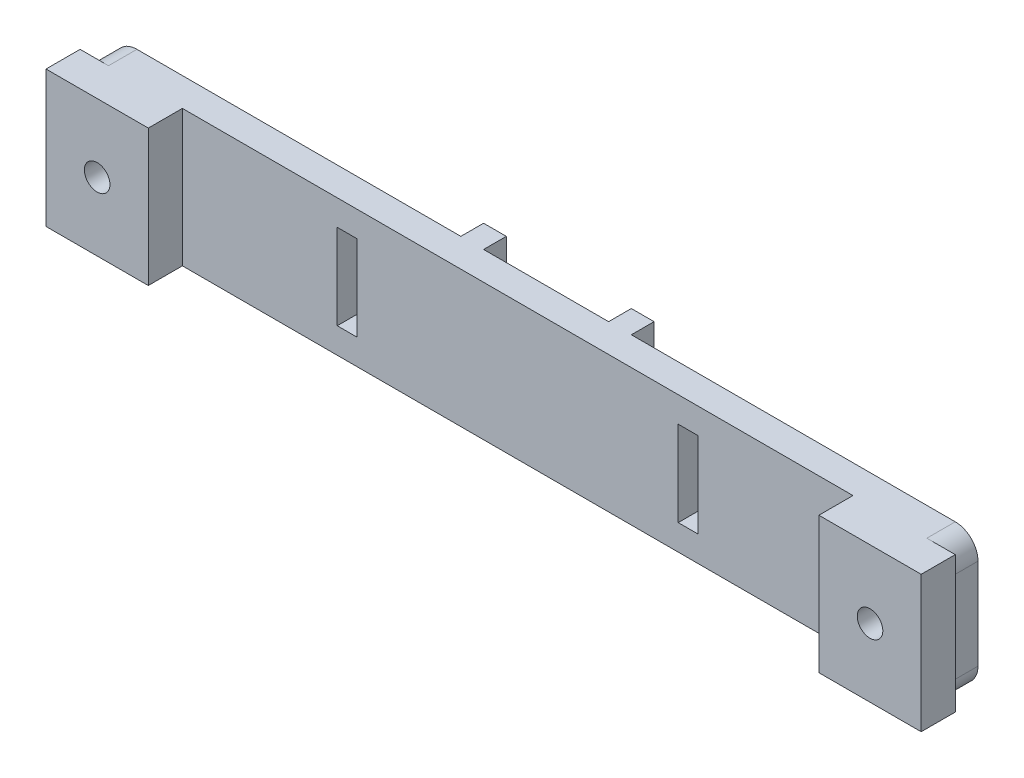
SolidWorks part; units mm, degrees
material "ABS"
ref_plane "Front Plane" through (0, 0, 0) normal (0, 0, 1) x (1, 0, 0)
ref_plane "Top Plane" through (0, 0, 0) normal (0, 1, 0) x (1, 0, 0)
ref_plane "Right Plane" through (0, 0, 0) normal (1, 0, 0) x (0, 0, -1)
sketch "Sketch1" plane through (0, 0, 0) normal (0, 0, 1) x (1, 0, 0)
  line L0 (-72, -12) -> (72, -12)
  line L1 (76, -8) -> (76, 8)
  line L2 (72, 12) -> (-72, 12)
  line L3 (-76, 8) -> (-76, -8)
  arc A0 (72, -12) -> (76, -8) centre (72, -8) ccw
  arc A1 (76, 8) -> (72, 12) centre (72, 8) ccw
  arc A2 (-72, 12) -> (-76, 8) centre (-72, 8) ccw
  arc A3 (-76, -8) -> (-72, -12) centre (-72, -8) ccw
extrude "Boss-Extrude1" add sketch "Sketch1" along normal blind 5
sketch "Sketch2" plane through (0, 0, 5) normal (0, 0, 1) x (1, 0, 0)
  line L0 (72, 12) -> (-72, 12) construction
  line L1 (-77, -12) -> (-59, -12)
  line L2 (-77, -12) -> (-77, 12)
  line L3 (-77, 12) -> (-59, 12)
  line L4 (-59, -12) -> (-59, 12)
  line L5 (-77, -12) -> (-59, 12) construction
  line L6 (-77, 12) -> (-59, -12) construction
  line L8 (59, -12) -> (77, -12)
  line L9 (59, -12) -> (59, 12)
  line L10 (59, 12) -> (77, 12)
  line L11 (77, -12) -> (77, 12)
  line L12 (59, -12) -> (77, 12) construction
  line L13 (59, 12) -> (77, -12) construction
  point P0 (-68, 0)
  point P7 (68, 0)
extrude "Boss-Extrude2" add sketch "Sketch2" along normal blind 6
sketch "Sketch3" plane through (0, 0, 11) normal (0, 0, 1) x (1, 0, 0)
  circle A0 centre (-68, 0) radius 2.25
  circle A1 centre (68, 0) radius 2.25
extrude "Cut-Extrude1" cut sketch "Sketch3" against normal through all
sketch "Sketch4" plane through (0, 0, 5) normal (0, 0, 1) x (1, 0, 0)
  line L1 (-31.75, -7.5) -> (-28.25, -7.5)
  line L2 (-31.75, -7.5) -> (-31.75, 7.5)
  line L3 (-31.75, 7.5) -> (-28.25, 7.5)
  line L4 (-28.25, -7.5) -> (-28.25, 7.5)
  line L5 (-31.75, -7.5) -> (-28.25, 7.5) construction
  line L6 (-31.75, 7.5) -> (-28.25, -7.5) construction
  line L7 (28.25, -7.5) -> (31.75, -7.5)
  line L8 (28.25, -7.5) -> (28.25, 7.5)
  line L9 (28.25, 7.5) -> (31.75, 7.5)
  line L10 (31.75, -7.5) -> (31.75, 7.5)
  line L11 (28.25, -7.5) -> (31.75, 7.5) construction
  line L12 (28.25, 7.5) -> (31.75, -7.5) construction
  point P0 (-30, 0)
  point P5 (30, 0)
extrude "Cut-Extrude2" cut sketch "Sketch4" against normal through all
sketch "Sketch5" plane through (0, 0, 0) normal (0, 0, 1) x (1, 0, 0)
  line L0 (59, 12) -> (-59, 12) construction
  line L1 (-15, -12) -> (-11, -12)
  line L2 (-15, -12) -> (-15, 12)
  line L3 (-15, 12) -> (-11, 12)
  line L4 (-11, -12) -> (-11, 12)
  line L5 (-15, -12) -> (-11, 12) construction
  line L6 (-15, 12) -> (-11, -12) construction
  line L8 (11, -12) -> (15, -12)
  line L9 (11, -12) -> (11, 12)
  line L10 (11, 12) -> (15, 12)
  line L11 (15, -12) -> (15, 12)
  line L12 (11, -12) -> (15, 12) construction
  line L13 (11, 12) -> (15, -12) construction
  point P0 (-13, 0)
  point P7 (13, 0)
extrude "Boss-Extrude3" add sketch "Sketch5" against normal blind 4
